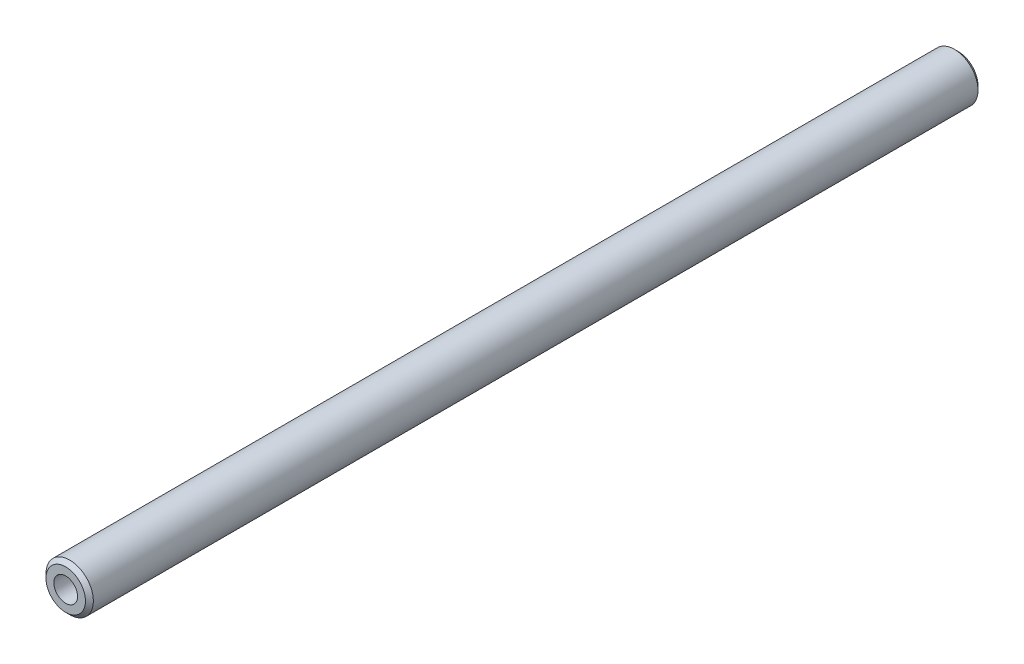
SolidWorks part; units mm, degrees
material "6061 合金"
ref_plane "前视基准面" through (0, 0, 0) normal (0, 0, 1) x (1, 0, 0)
ref_plane "上视基准面" through (0, 0, 0) normal (0, 1, 0) x (1, 0, 0)
ref_plane "右视基准面" through (0, 0, 0) normal (1, 0, 0) x (0, 0, -1)
other "Configuration Table"
sketch "草图1" plane through (0, 0, 0) normal (0, 0, 1) x (1, 0, 0)
  circle A0 centre (0, 0) radius 3
  circle A1 centre (0, 0) radius 6
  dimension "D1" = 6
  dimension "D2" = 12
extrude "凸台-拉伸1" add sketch "草图1" along normal blind 226
chamfer "倒角1" distance 1 angle 45 2 edges at (6, 0, 226) (6, 0, 0)
